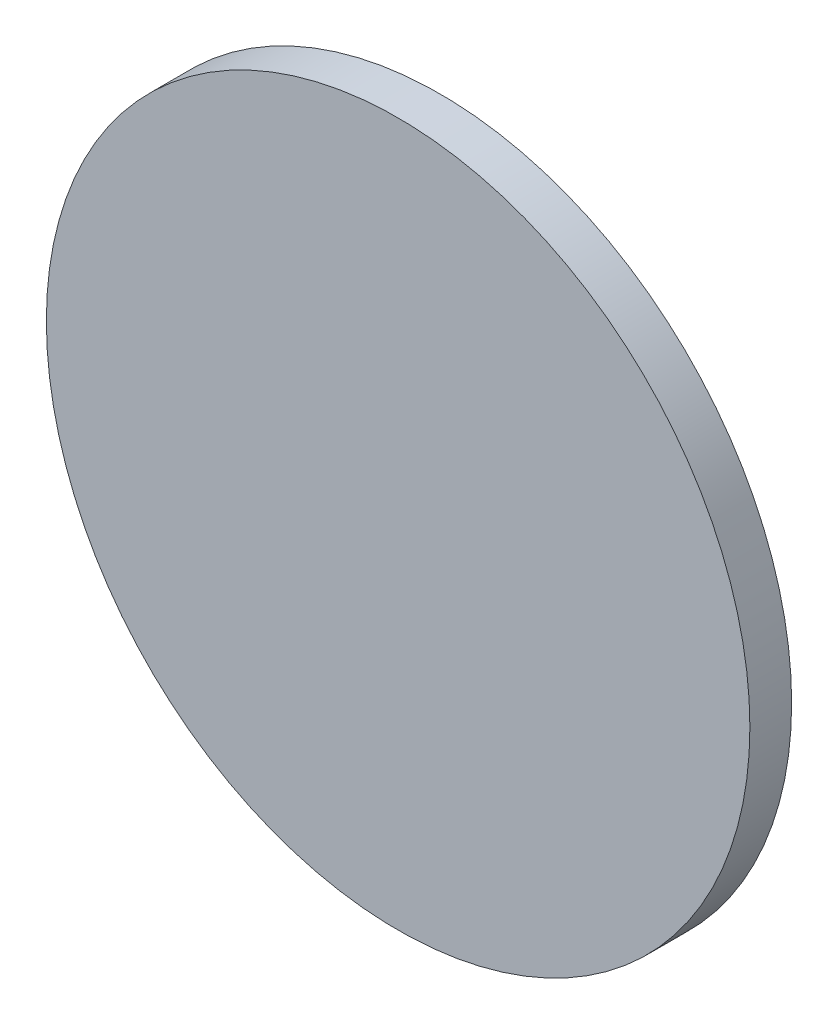
SolidWorks part; units mm, degrees
ref_plane "Front Plane" through (0, 0, 0) normal (0, 0, 1) x (1, 0, 0)
ref_plane "Top Plane" through (0, 0, 0) normal (0, 1, 0) x (1, 0, 0)
ref_plane "Right Plane" through (0, 0, 0) normal (1, 0, 0) x (0, 0, -1)
sketch "Sketch1" plane through (0, 0, 0) normal (0, 0, 1) x (1, 0, 0)
  circle A0 centre (0, 0) radius 84.251
extrude "Boss-Extrude1" add sketch "Sketch1" along normal blind 10
